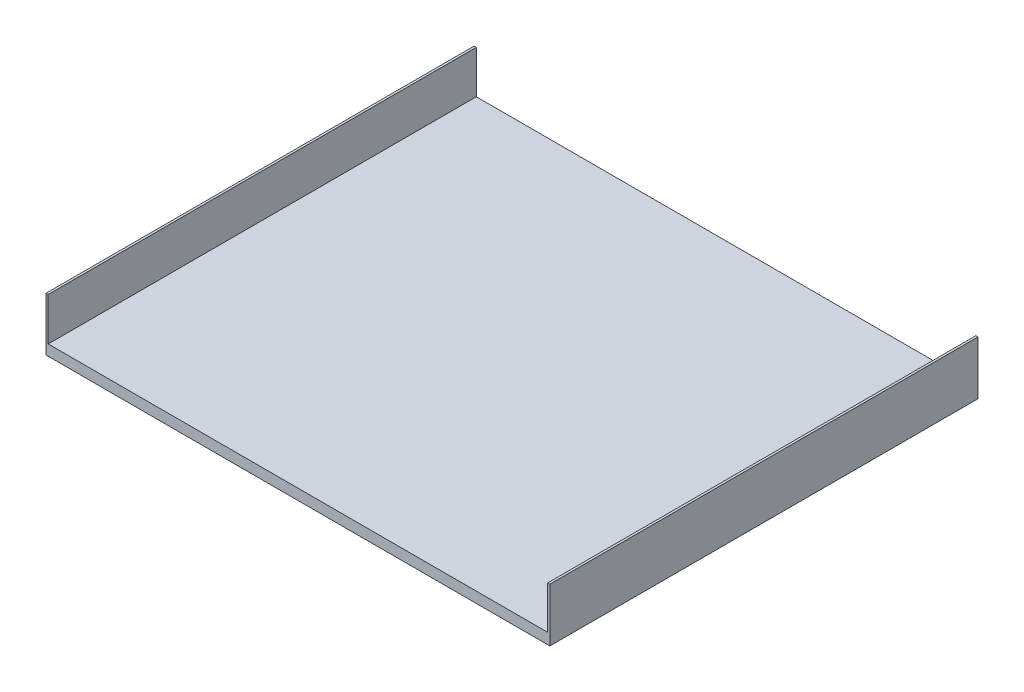
SolidWorks part; units mm, degrees
ref_plane "Alzado" through (0, 0, 0) normal (0, 0, 1) x (1, 0, 0)
ref_plane "Planta" through (0, 0, 0) normal (0, 1, 0) x (1, 0, 0)
ref_plane "Vista lateral" through (0, 0, 0) normal (1, 0, 0) x (0, 0, -1)
sketch "Croquis1" plane through (0, 0, 0) normal (0, 0, 1) x (1, 0, 0)
  line L0 (350, 0) -> (-350, 0)
  line L1 (-350, 0) -> (-350, 60)
  line L2 (-350, 60) -> (-353.0625, 60)
  line L3 (-353.0625, 60) -> (-353.0625, -15)
  line L4 (-353.0625, -15) -> (353.0625, -15)
  line L5 (0, -15) -> (0, 0)
  line L6 (353.0625, 60) -> (353.0625, -15)
  line L7 (350, 60) -> (353.0625, 60)
  line L8 (350, 0) -> (350, 60)
  dimension "D1" = 350
  dimension "D2" = 3.0625
  dimension "D3" = 15
  dimension "D4" = 75
extrude "Saliente-Extruir1" add sketch "Croquis1" along normal mid plane 600 contours L4 L5 L0 L1 L2 L3 | L8 L0 L5 L4 L6 L7
